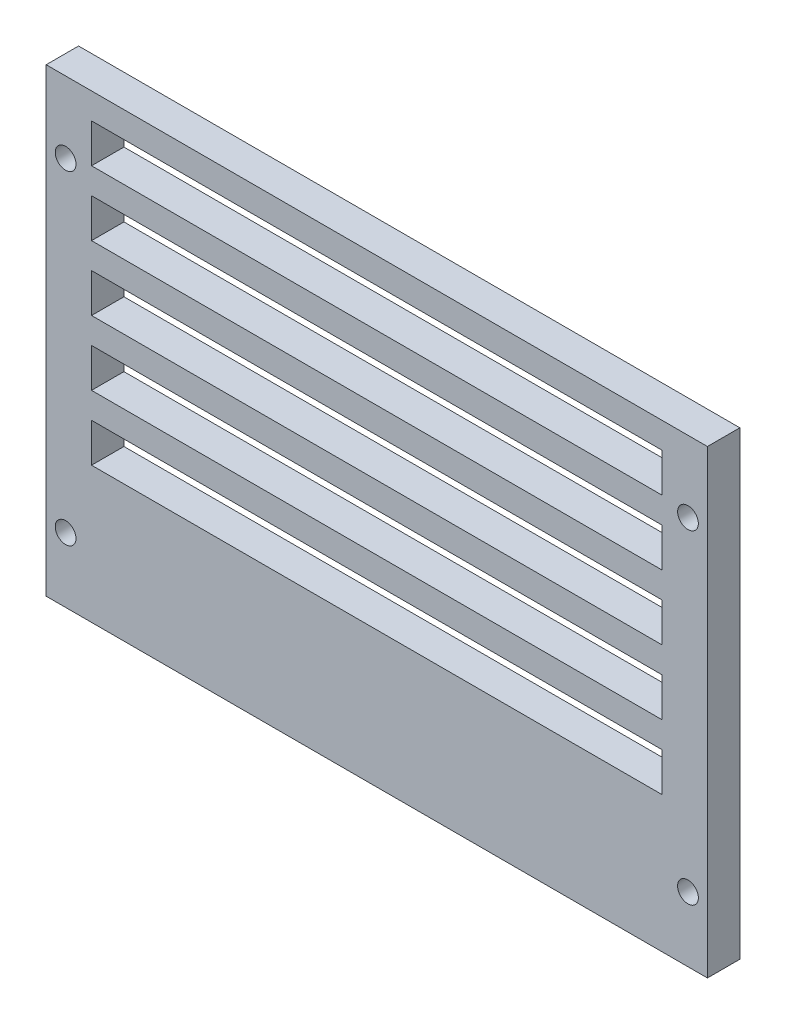
SolidWorks part; units mm, degrees
ref_plane "Front" through (0, 0, 0) normal (0, 0, 1) x (1, 0, 0)
ref_plane "Top" through (0, 0, 0) normal (0, 1, 0) x (1, 0, 0)
ref_plane "Right" through (0, 0, 0) normal (1, 0, 0) x (0, 0, -1)
sketch "草图1" plane through (0, 0, 0) normal (0, 0, 1) x (1, 0, 0)
  line L1 (0, 0) -> (102, 0)
  line L2 (0, 0) -> (0, 65)
  line L3 (0, 65) -> (102, 65)
  line L4 (102, 0) -> (102, 65)
  dimension "D1" = 102
  dimension "D2" = 65
extrude "凸台-拉伸1" add sketch "草图1" along normal blind 5
sketch "草图2" plane through (0, 0, 5) normal (0, 0, 1) x (1, 0, 0)
  line L0 (0, 65) -> (0, 0) construction
  line L1 (102, 65) -> (0, 65) construction
  line L2 (102, 0) -> (102, 65) construction
  line L3 (0, 0) -> (102, 0) construction
  circle A0 centre (3, 60) radius 1.6
  circle A1 centre (99, 10) radius 1.6
  circle A2 centre (3, 10) radius 1.6
  circle A3 centre (99, 60) radius 1.6
  dimension "D1" = 3
  dimension "D2" = 5
  dimension "D3" = 3
  dimension "D4" = 10
  dimension "D5" = 10
  dimension "D6" = 5
extrude "切除-拉伸1" cut sketch "草图2" against normal through all
sketch "草图3" plane through (0, 0, 5) normal (0, 0, 1) x (1, 0, 0)
  line L1 (0, 65) -> (102, 65)
  line L2 (0, 65) -> (0, 71)
  line L3 (0, 71) -> (102, 71)
  line L4 (102, 65) -> (102, 71)
  dimension "D1" = 6
extrude "凸台-拉伸2" add sketch "草图3" against normal blind 5
sketch "草图4" plane through (0, 0, 5) normal (0, 0, 1) x (1, 0, 0)
  line L0 (102, 71) -> (0, 71) construction
  line L1 (7, 67) -> (95, 67)
  line L2 (7, 67) -> (7, 61)
  line L3 (7, 61) -> (95, 61)
  line L4 (95, 67) -> (95, 61)
  line L5 (0, 71) -> (0, 0) construction
  line L6 (102, 0) -> (102, 71) construction
  dimension "D1" = 4
  dimension "D2" = 7
  dimension "D3" = 6
  dimension "D4" = 7
extrude "切除-拉伸2" cut sketch "草图4" against normal through all
pattern_linear "阵列(线性)1" count 5 spacing 10 along (0, -1, 0) of "切除-拉伸2"
